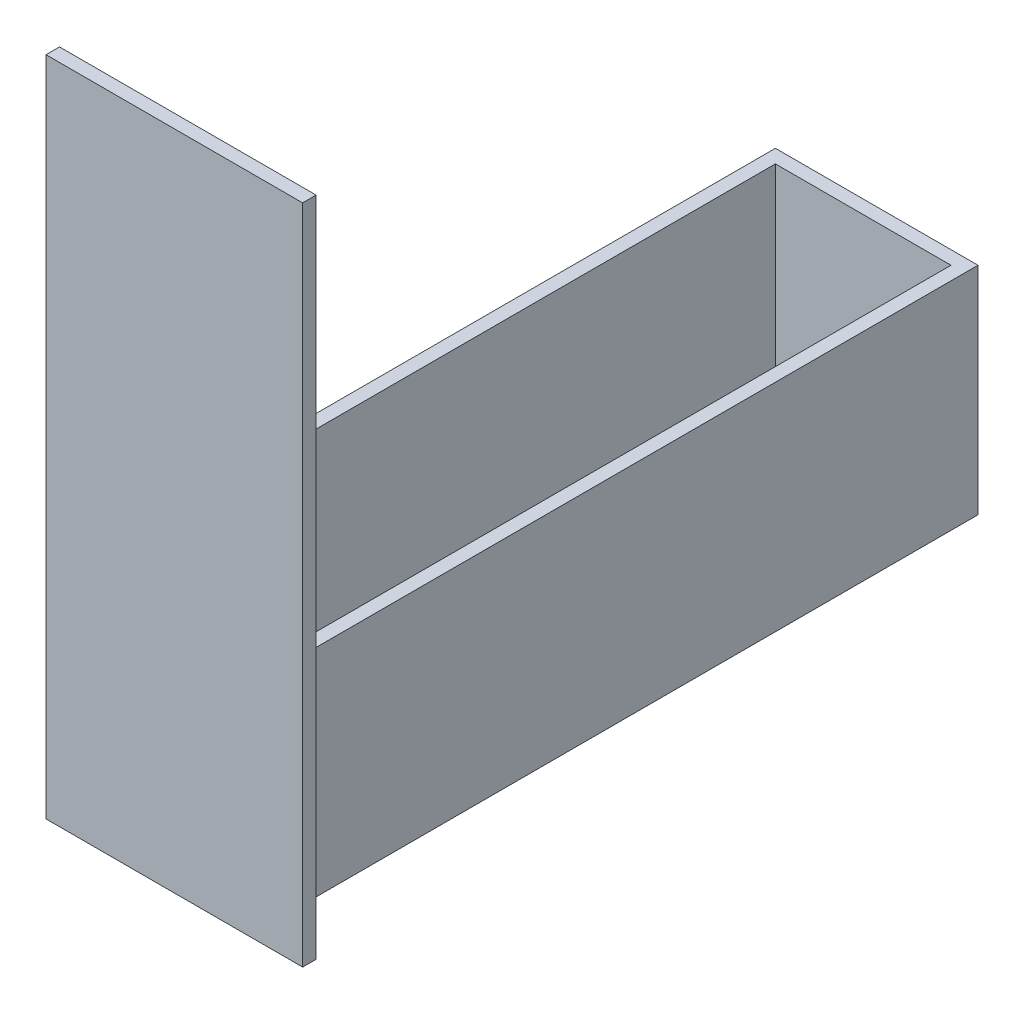
SolidWorks part; units mm, degrees
ref_plane "Спереди" through (0, 0, 0) normal (0, 0, 1) x (1, 0, 0)
ref_plane "Сверху" through (0, 0, 0) normal (0, 1, 0) x (1, 0, 0)
ref_plane "Справа" through (0, 0, 0) normal (1, 0, 0) x (0, 0, -1)
sketch "Эскиз1" plane through (0, 0, 0) normal (0, 0, 1) x (1, 0, 0)
  line L1 (0, 0) -> (190, 0)
  line L2 (0, 0) -> (0, 490)
  line L3 (0, 490) -> (190, 490)
  line L4 (190, 0) -> (190, 490)
  dimension "D1" = 490
  dimension "D2" = 190
extrude "Бобышка-Вытянуть1" add sketch "Эскиз1" along normal blind 10
sketch "Эскиз2" plane through (0, 0, 0) normal (0, 0, -1) x (-1, 0, 0)
  line L0 (-170, 180) -> (-170, 20)
  line L1 (-170, 20) -> (-20, 20)
  line L2 (-20, 20) -> (-20, 180)
  line L3 (-20, 180) -> (-30, 180)
  line L4 (-30, 180) -> (-30, 30)
  line L5 (-30, 30) -> (-160, 30)
  line L6 (-160, 30) -> (-160, 180)
  line L7 (-160, 180) -> (-170, 180)
  line L8 (-170, 20) -> (-170, 0) construction
  line L10 (0, 0) -> (-190, 0) construction
  line L11 (-190, 20) -> (-170, 20) construction
  line L12 (-190, 0) -> (-190, 490) construction
  line L13 (-20, 20) -> (0, 20) construction
  line L14 (0, 490) -> (0, 0) construction
  line L15 (-160, 30) -> (-160, 20) construction
  dimension "D1" = 10
  dimension "D2" = 20
  dimension "D3" = 150
extrude "Бобышка-Вытянуть2" add sketch "Эскиз2" along normal blind 500
sketch "Эскиз3" plane through (0, 0, -500) normal (0, 0, -1) x (-1, 0, 0)
  line L1 (-170, 180) -> (-20, 180)
  line L2 (-170, 180) -> (-170, 20)
  line L3 (-170, 20) -> (-20, 20)
  line L4 (-20, 180) -> (-20, 20)
extrude "Бобышка-Вытянуть3" add sketch "Эскиз3" along normal blind 10
